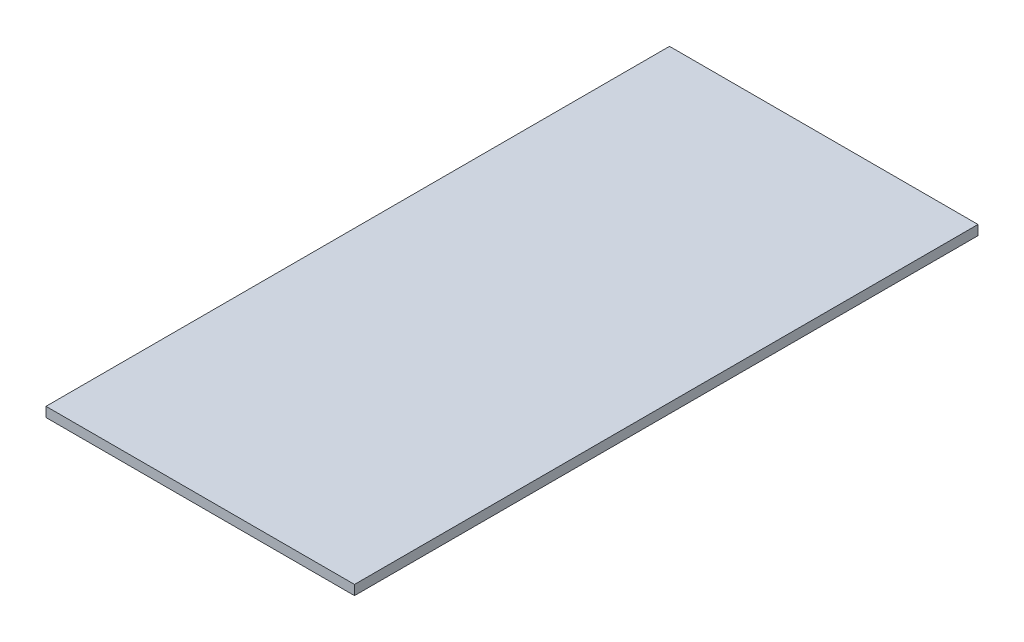
SolidWorks part; units mm, degrees
ref_plane "Front Plane" through (0, 0, 0) normal (0, 0, 1) x (1, 0, 0)
ref_plane "Top Plane" through (0, 0, 0) normal (0, 1, 0) x (1, 0, 0)
ref_plane "Right Plane" through (0, 0, 0) normal (1, 0, 0) x (0, 0, -1)
sketch "Sketch1" plane through (0, 0, 0) normal (0, 1, 0) x (1, 0, 0)
  line L1 (0, 0) -> (603.25, 0)
  line L2 (0, 0) -> (0, 1219.2)
  line L3 (0, 1219.2) -> (603.25, 1219.2)
  line L4 (603.25, 0) -> (603.25, 1219.2)
  dimension "D1" = 603.25
  dimension "D2" = 1219.2
extrude "Boss-Extrude1" add sketch "Sketch1" along normal blind 19.05
